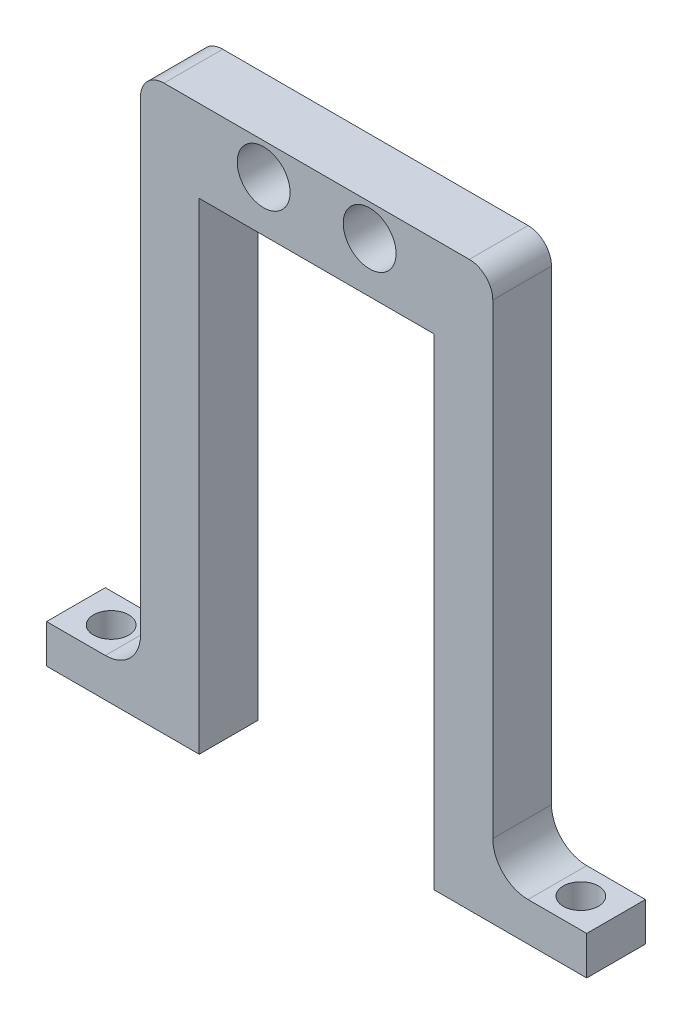
SolidWorks part; units mm, degrees
ref_plane "Plan de face" through (0, 0, 0) normal (0, 0, 1) x (1, 0, 0)
ref_plane "Plan de dessus" through (0, 0, 0) normal (0, 1, 0) x (1, 0, 0)
ref_plane "Plan de droite" through (0, 0, 0) normal (1, 0, 0) x (0, 0, -1)
sketch "Sketch1" plane through (0, 0, 0) normal (0, 0, 1) x (1, 0, 0)
  line L1 (0, 0) -> (20, 0)
  line L2 (0, 0) -> (0, 41)
  line L3 (0, 41) -> (20, 41)
  line L4 (20, 0) -> (20, 41)
  line L5 (-5, 0) -> (25, 0)
  line L6 (-5, 0) -> (-5, 48)
  line L7 (-5, 48) -> (25, 48)
  line L8 (25, 0) -> (25, 48)
  line L9 (20, 0) -> (33, 0)
  line L10 (20, 0) -> (20, 3.288)
  line L11 (20, 3.288) -> (33, 3.288)
  line L12 (33, 0) -> (33, 3.288)
  line L13 (0, 0) -> (-13, 0)
  line L14 (0, 0) -> (0, 3.288)
  line L15 (0, 3.288) -> (-13, 3.288)
  line L16 (-13, 0) -> (-13, 3.288)
  dimension "D1" = 41
  dimension "D2" = 20
  dimension "D3" = 30
  dimension "D4" = 7
  dimension "D5" = 5
  dimension "D7" = 13
  dimension "D8" = 13
extrude "Boss-Extrude1" add sketch "Sketch1" against normal blind 5 contours L15 L2 L3 L4 L11 L8 L7 L6 | L2 L15 L6 L5 | L16 L13 L6 L15 | L11 L4 L5 L8 | L9 L12 L11 L8
fillet "Fillet1" radius 2 2 edges at (-5, 48, -2.5) (25, 48, -2.5)
sketch "Sketch2" plane through (0, 3.288, 0) normal (0, 1, 0) x (1, 0, 0)
  line L1 (33, 5) -> (33, 0) construction
  line L2 (-13, 5) -> (-13, 0) construction
  circle A0 centre (-10, 2.5) radius 1.5
  circle A1 centre (30, 2.5) radius 1.5
  dimension "D1" = 3
  dimension "D2" = 3
  dimension "D3" = 3
  dimension "D4" = 3
extrude "Cut-Extrude1" cut sketch "Sketch2" against normal through all both and the other way through all
sketch "Sketch3" plane through (0, 0, 0) normal (0, 0, 1) x (1, 0, 0)
  line L0 (0, 41) -> (20, 41) construction
  line L1 (10, 48) -> (10, 39.7) construction
  line L2 (-3, 48) -> (23, 48) construction
  circle A0 centre (14.5135, 45.3) radius 2.25
  circle A1 centre (5.4865, 45.3) radius 2.25
  dimension "D1" = 4.5
  dimension "D2" = 4.3
extrude "Cut-Extrude2" cut sketch "Sketch3" against normal through all both and the other way through all
fillet "Fillet2" radius 3 2 edges at (25, 3.288, -2.5) (-5, 3.288, -2.5)
